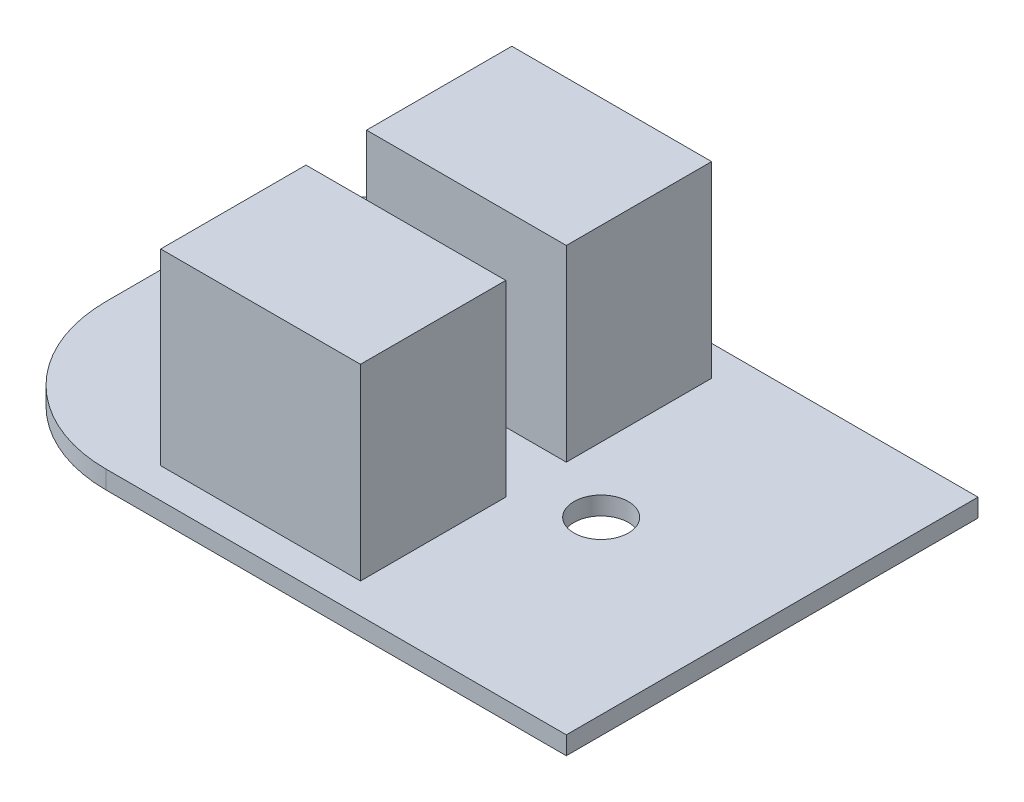
SolidWorks part; units mm, degrees
ref_plane "Front Plane" through (0, 0, 0) normal (0, 0, 1) x (1, 0, 0)
ref_plane "Top Plane" through (0, 0, 0) normal (0, 1, 0) x (1, 0, 0)
ref_plane "Right Plane" through (0, 0, 0) normal (1, 0, 0) x (0, 0, -1)
sketch "Sketch1" plane through (0, 0, 0) normal (0, 1, 0) x (1, 0, 0)
  line L1 (0, 0) -> (50, 0)
  line L2 (0, 0) -> (0, -34)
  line L3 (0, -34) -> (50, -34)
  line L4 (50, 0) -> (50, -34)
  dimension "D1" = 34
  dimension "D2" = 50
extrude "Boss-Extrude1" add sketch "Sketch1" along normal blind 1.5
fillet "Fillet1" radius 12 2 edges at (0, 0.75, 0) (0, 0.75, 34)
sketch "Sketch2" plane through (0, 1.5, 0) normal (0, 1, 0) x (1, 0, 0)
  line L0 (50, -34) -> (50, 0) construction
  line L1 (50, 0) -> (12, 0) construction
  circle A0 centre (8.04, -17) radius 2.25
  circle A1 centre (35.88, -17) radius 2.25
  dimension "D1" = 4.5
  dimension "D2" = 4.5
  dimension "D3" = 14.12
  dimension "D4" = 17
  dimension "D5" = 17
  dimension "D6" = 27.84
extrude "Cut-Extrude1" cut sketch "Sketch2" against normal blind 1.5
sketch "Sketch3" plane through (0, 1.5, 0) normal (0, 1, 0) x (1, 0, 0)
  line L0 (50, 0) -> (12, 0) construction
  line L1 (14, -2.5) -> (30.5, -2.5)
  line L2 (14, -2.5) -> (14, -14.5)
  line L3 (14, -14.5) -> (30.5, -14.5)
  line L4 (30.5, -2.5) -> (30.5, -14.5)
  line L5 (50, -34) -> (50, 0) construction
  line L6 (50, -17) -> (42.2871, -17) construction
  line L7 (30.5, -31.5) -> (30.5, -19.5)
  line L8 (14, -31.5) -> (30.5, -31.5)
  line L9 (14, -31.5) -> (14, -19.5)
  line L10 (14, -19.5) -> (30.5, -19.5)
  dimension "D1" = 16.5
  dimension "D2" = 12
  dimension "D3" = 2.5
  dimension "D4" = 36
extrude "Boss-Extrude2" add sketch "Sketch3" along normal blind 15.5
equation "\"D3@Sketch2\"=11.87+4.5/2"
equation "\"D4@Sketch2\"=\"D1@Sketch1\"/2"
equation "\"D5@Sketch2\"=\"D4@Sketch2\""
equation "\"D6@Sketch2\"=23.34+4.5"
